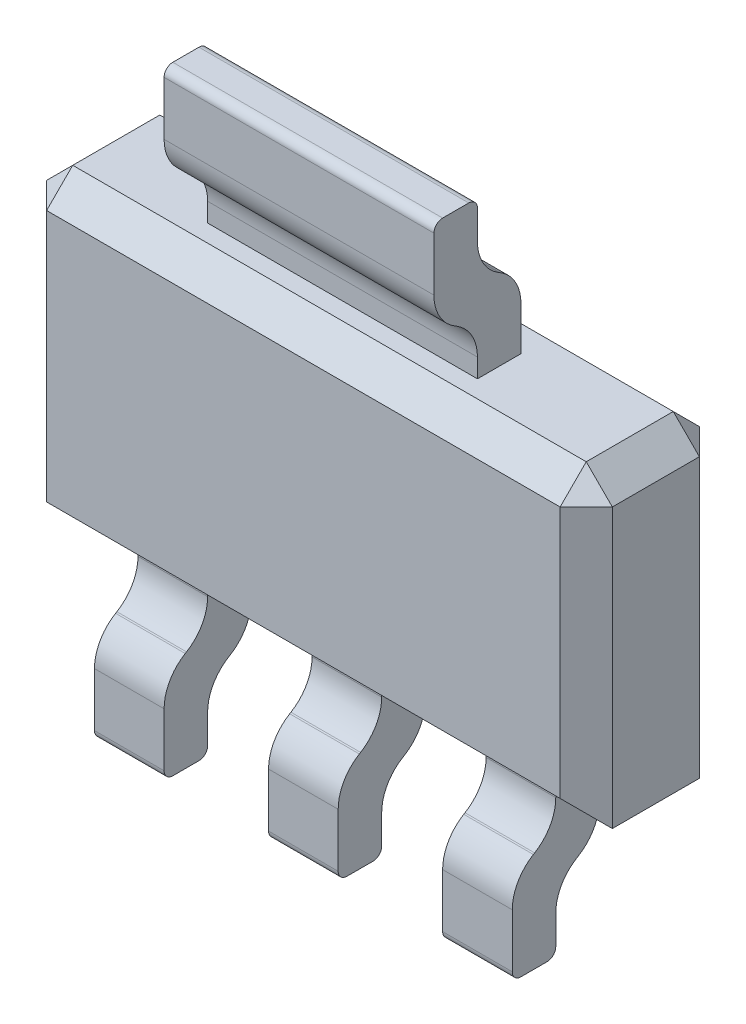
SolidWorks part; units mm, degrees
ref_plane "Front Plane" through (0, 0, 0) normal (0, 0, 1) x (1, 0, 0)
ref_plane "Top Plane" through (0, 0, 0) normal (0, 1, 0) x (1, 0, 0)
ref_plane "Right Plane" through (0, 0, 0) normal (1, 0, 0) x (0, 0, -1)
sketch "Sketch1" plane through (0, 0, 0) normal (0, 0, 1) x (1, 0, 0)
  line L1 (-3.25, 1.75) -> (3.25, 1.75)
  line L2 (-3.25, 1.75) -> (-3.25, -1.75)
  line L3 (-3.25, -1.75) -> (3.25, -1.75)
  line L4 (3.25, 1.75) -> (3.25, -1.75)
  line L5 (-3.25, 1.75) -> (3.25, -1.75) construction
  line L6 (-3.25, -1.75) -> (3.25, 1.75) construction
  point P0 (0, 0)
  dimension "D1" = 6.5
  dimension "D2" = 3.5
extrude "Boss-Extrude1" add sketch "Sketch1" along normal blind 1.6
chamfer "Chamfer1" distance 0.3 angle 45 10 edges at (3.25, 0, 0) (3.25, 1.75, 0.8) (0, 1.75, 0) (0, -1.75, 0) (-3.25, 0, 0) (-3.25, 1.75, 0.8) (0, -1.75, 1.6) (3.25, 0, 1.6) (0, 1.75, 1.6) (-3.25, 0, 1.6)
sketch "Sketch2" plane through (0, 0, 0) normal (1, 0, 0) x (0, 0, -1)
  line L0 (-1.1, 1.75) -> (-1.1, 1.9669)
  line L1 (-1.3, 1.75) -> (-0.3, 1.75) construction
  line L2 (-1.3428, 2.3957) -> (-1.3572, 2.4043)
  line L3 (-1.6, 2.8331) -> (-1.6, 3.45)
  line L4 (-1.5, 3.55) -> (-1.2, 3.55)
  line L5 (-1.1, 3.45) -> (-1.1, 3.1162)
  line L6 (-0.8572, 2.6874) -> (-0.8428, 2.6787)
  line L7 (-0.6, 2.25) -> (-0.6, 1.75)
  line L8 (-1.3, 1.75) -> (-1.3, 1.45) construction
  line L9 (-0.3, 1.75) -> (-0.6, 1.75)
  line L13 (-1.3, 1.75) -> (-1.3, 1.45)
  line L14 (-1.3, 1.45) -> (-0.3, 1.45)
  line L15 (-0.3, 1.45) -> (-0.3, 1.75)
  line L16 (-0.3, 1.75) -> (-1.3, 1.75)
  line L17 (-1.3, 1.75) -> (-1.3, 1.45)
  line L18 (-1.3, 1.45) -> (-0.3, 1.45)
  line L19 (-0.3, 1.45) -> (-0.3, 1.75)
  line L20 (-1.1, 1.75) -> (-1.3, 1.75)
  arc A0 (-1.6, 2.8331) -> (-1.3572, 2.4043) centre (-1.1, 2.8331) ccw
  arc A1 (-1.3428, 2.3957) -> (-1.1, 1.9669) centre (-1.6, 1.9669) cw
  arc A2 (-0.6, 2.25) -> (-0.8428, 2.6787) centre (-1.1, 2.25) ccw
  arc A3 (-0.8572, 2.6874) -> (-1.1, 3.1162) centre (-0.6, 3.1162) cw
  arc A4 (-1.1, 3.45) -> (-1.2, 3.55) centre (-1.2, 3.45) ccw
  arc A5 (-1.5, 3.55) -> (-1.6, 3.45) centre (-1.5, 3.45) ccw
  point P14 (-1.6, 2.55)
  point P17 (-1.1, 2.25)
  point P26 (-1.6, 3.55)
  dimension "D8" = 0.5
  dimension "D9" = 0.1
  dimension "D1" = 1.8
  dimension "D2" = 1
  dimension "D3" = 0.5
  dimension "D4" = 0.5
  dimension "D5" = 0.5
  dimension "D6" = 0.5
  dimension "D7" = 0.2
  dimension "D10" = 0
extrude "Boss-Extrude2" add sketch "Sketch2" along normal blind 1.5 and the other way blind 1.6
sketch "Sketch3" plane through (0, 0, 0) normal (1, 0, 0) x (0, 0, -1)
  line L0 (0, 0) -> (-3.2094, 0) construction
  line L2 (-1.1, -1.75) -> (-1.1, -1.9669)
  line L3 (-1.3, -1.75) -> (-0.3, -1.75) construction
  line L4 (-1.3428, -2.3957) -> (-1.3572, -2.4043)
  line L5 (-1.6, -2.8331) -> (-1.6, -3.45)
  line L6 (-1.5, -3.55) -> (-1.2, -3.55)
  line L7 (-1.1, -3.45) -> (-1.1, -3.1162)
  line L8 (-0.8572, -2.6874) -> (-0.8428, -2.6787)
  line L9 (-0.6, -2.25) -> (-0.6, -1.75)
  line L10 (-0.6, -1.75) -> (-1.1, -1.75)
  line L11 (-1.3, 1.45) -> (-1.3, -1.75) construction
  arc A0 (-0.8428, -2.6787) -> (-0.6, -2.25) centre (-1.1, -2.25) ccw
  arc A1 (-1.1, -3.1162) -> (-0.8572, -2.6874) centre (-0.6, -3.1162) cw
  arc A2 (-1.3572, -2.4043) -> (-1.6, -2.8331) centre (-1.1, -2.8331) ccw
  arc A3 (-1.1, -1.9669) -> (-1.3428, -2.3957) centre (-1.6, -1.9669) cw
  arc A4 (-1.2, -3.55) -> (-1.1, -3.45) centre (-1.2, -3.45) ccw
  arc A5 (-1.6, -3.45) -> (-1.5, -3.55) centre (-1.5, -3.45) ccw
  point P21 (-1.6, -2.55)
  point P24 (-1.1, -2.25)
  point P29 (-1.6, -3.55)
  dimension "D8" = 0.5
  dimension "D9" = 0.1
  dimension "D1" = 1.8
  dimension "D2" = 1
  dimension "D3" = 0.5
  dimension "D4" = 0.5
  dimension "D5" = 0.5
  dimension "D6" = 0.2
  dimension "D7" = 0.5
extrude "Boss-Extrude3" add sketch "Sketch3" along normal blind 0.4 and the other way blind 0.4
pattern_linear "LPattern1" count 2 spacing 2 along (-1, 0, 0) count 2 spacing 2 along (1, 0, 0) of "Boss-Extrude3"
sketch "Sketch4" plane through (0, 0, 0) normal (0, 0, -1) x (-1, 0, 0)
  text T0 "<i>SOT</i>" font "Century Gothic" height 1
extrude "Cut-Extrude1" cut sketch "Sketch4" against normal blind 0.1
